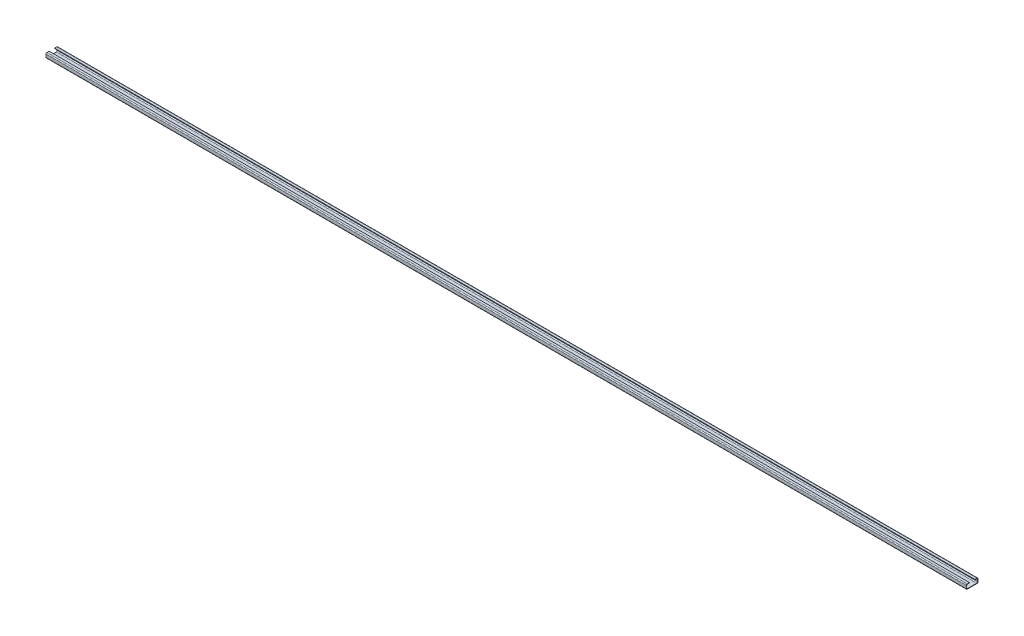
SolidWorks part; units mm, degrees
material "AISI 1045 Aço, trefilado"
ref_plane "Plano frontal" through (0, 0, 0) normal (0, 0, 1) x (1, 0, 0)
ref_plane "Plano superior" through (0, 0, 0) normal (0, 1, 0) x (1, 0, 0)
ref_plane "Plano direito" through (0, 0, 0) normal (1, 0, 0) x (0, 0, -1)
sketch "Esboço1" plane through (0, 0, 0) normal (1, 0, 0) x (0, 0, -1)
  line L0 (-34.75, 12.25) -> (-34.75, -12.25)
  line L1 (-37.5, 15) -> (-17.5, 15)
  line L2 (-37.5, 15) -> (-37.5, -15)
  line L3 (-37.5, -15) -> (37.5, -15)
  line L4 (37.5, 15) -> (37.5, -15)
  line L5 (-37.5, 15) -> (37.5, -15) construction
  line L6 (-37.5, -15) -> (37.5, 15) construction
  line L7 (-34.75, -12.25) -> (34.75, -12.25)
  line L8 (34.75, 12.25) -> (34.75, -12.25)
  line L9 (-34.75, 12.25) -> (-17.5, 12.25)
  line L10 (-17.5, 15) -> (-17.5, 12.25)
  line L13 (17.5, 15) -> (17.5, 12.25)
  line L14 (17.5, 12.25) -> (34.75, 12.25)
  line L15 (-34.75, 12.25) -> (34.75, 12.25) construction
  line L16 (17.5, 15) -> (37.5, 15)
  line L17 (-37.5, 15) -> (37.5, 15) construction
  point P0 (0, 0)
  dimension "D1" = 75
  dimension "D2" = 30
  dimension "D4" = 20
  dimension "D5" = 20
  dimension "D3" = 2.75
extrude "Ressalto-extrusão1" add sketch "Esboço1" along normal blind 5900
fillet "Filete1" radius 6 8 edges at (2950, 12.25, -34.75) (2950, 12.25, 34.75) (2950, 15, 37.5) (2950, 15, -37.5) (2950, -15, -37.5) (2950, -12.25, -34.75) (2950, -12.25, 34.75) (2950, -15, 37.5)
